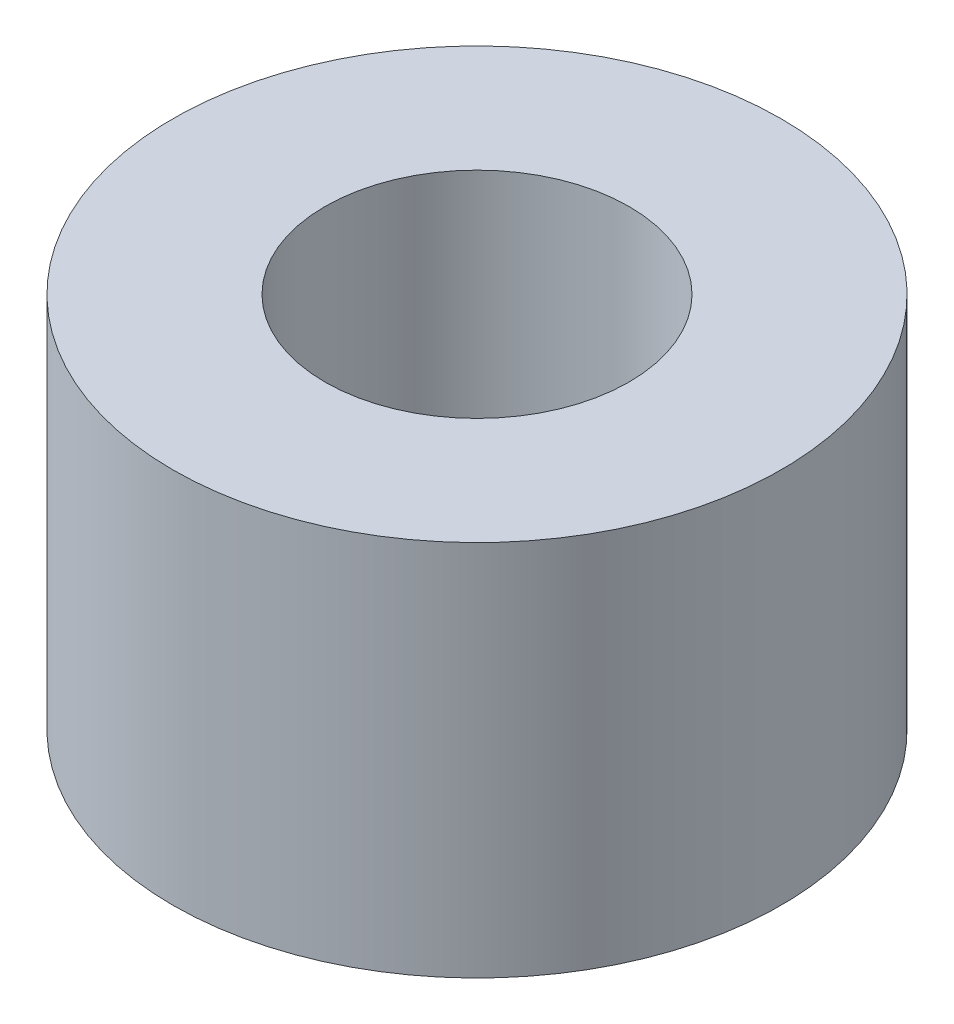
SolidWorks part; units mm, degrees
material "PET"
ref_plane "Front" through (0, 0, 0) normal (0, 0, 1) x (1, 0, 0)
ref_plane "Top" through (0, 0, 0) normal (0, 1, 0) x (1, 0, 0)
ref_plane "Right" through (0, 0, 0) normal (1, 0, 0) x (0, 0, -1)
sketch "Sketch1" plane through (0, 0, 0) normal (0, 1, 0) x (1, 0, 0)
  circle A0 centre (0, 0) radius 3.175
  circle A1 centre (0, 0) radius 6.35
  dimension "D1" = 6.35
  dimension "D2" = 3.175
extrude "Boss-Extrude1" add sketch "Sketch1" along normal blind 7.874
